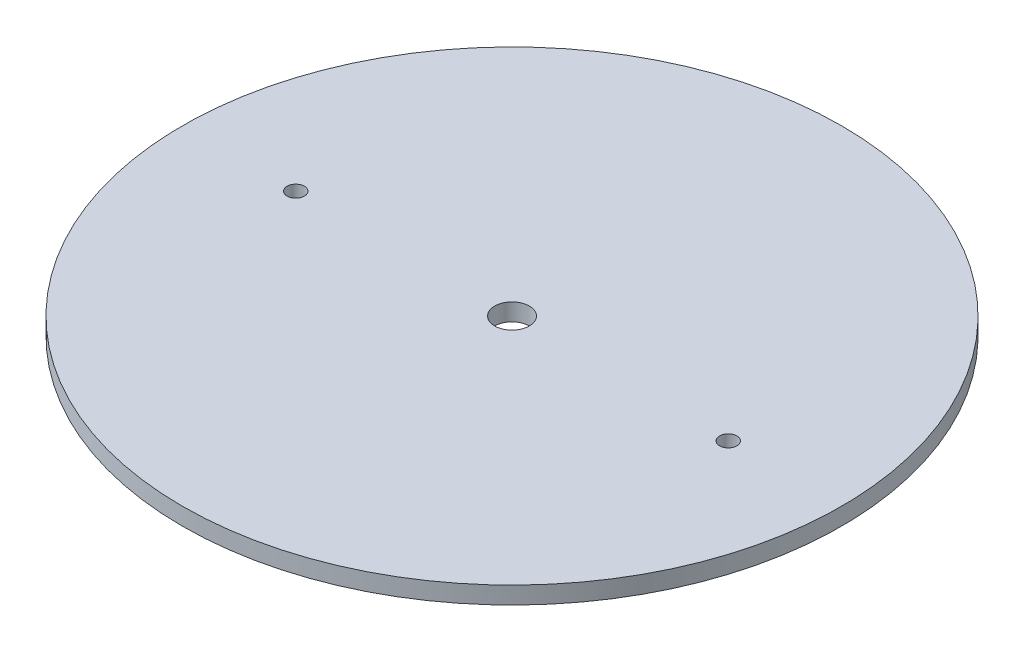
SolidWorks part; units mm, degrees
ref_plane "Front Plane" through (0, 0, 0) normal (0, 0, 1) x (1, 0, 0)
ref_plane "Top Plane" through (0, 0, 0) normal (0, 1, 0) x (1, 0, 0)
ref_plane "Right Plane" through (0, 0, 0) normal (1, 0, 0) x (0, 0, -1)
sketch "Sketch1" plane through (0, 0, 0) normal (0, 1, 0) x (1, 0, 0)
  line L0 (0, 0) -> (-50, 0) construction
  line L1 (0, 0) -> (0, -18.6216) construction
  circle A0 centre (0, 0) radius 76.2
  circle A1 centre (0, 0) radius 4
  circle A2 centre (-50, 0) radius 2
  circle A3 centre (50, 0) radius 2
  dimension "D1" = 8
  dimension "D2" = 152.4
  dimension "D3" = 4
  dimension "D4" = 50
extrude "Boss-Extrude1" add sketch "Sketch1" along normal blind 4
